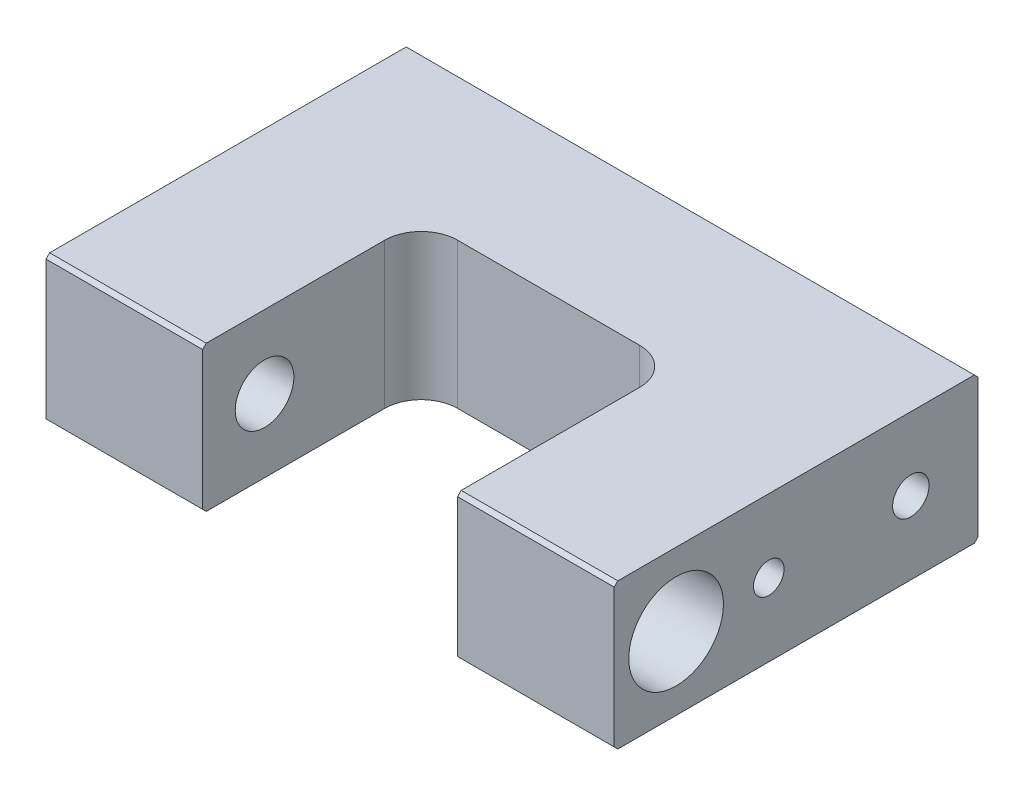
SolidWorks part; units mm, degrees
ref_plane "Front Plane" through (0, 0, 0) normal (0, 0, 1) x (1, 0, 0)
ref_plane "Top Plane" through (0, 0, 0) normal (0, 1, 0) x (1, 0, 0)
ref_plane "Right Plane" through (0, 0, 0) normal (1, 0, 0) x (0, 0, -1)
other "Configuration Table"
sketch "草图1" plane through (0, 0, 0) normal (0, 1, 0) x (1, 0, 0)
  line L1 (-39, 27.2208) -> (39, 27.2208)
  line L2 (-39, 27.2208) -> (-39, -27.2208)
  line L3 (-39, -27.2208) -> (39, -27.2208)
  line L4 (39, 27.2208) -> (39, -27.2208)
  line L5 (-39, 27.2208) -> (39, -27.2208) construction
  line L6 (-39, -27.2208) -> (39, 27.2208) construction
  point P0 (0, 0)
  dimension "D1" = 78
extrude "凸台-拉伸1" add sketch "草图1" along normal blind 20
sketch "草图2" plane through (0, 20, 0) normal (0, 1, 0) x (1, 0, 0)
  line L0 (0, 0) -> (0, -27.2208) construction
  line L1 (-39, -27.2208) -> (39, -27.2208) construction
  line L2 (-17.5, -27.2208) -> (17.5, -27.2208)
  line L3 (-17.5, -27.2208) -> (-17.5, -2.2208)
  line L4 (-12.5, 2.7792) -> (12.5, 2.7792)
  line L5 (17.5, -2.2208) -> (17.5, -27.2208)
  arc A0 (17.5, -2.2208) -> (12.5, 2.7792) centre (12.5, -2.2208) ccw
  arc A1 (-17.5, -2.2208) -> (-12.5, 2.7792) centre (-12.5, -2.2208) cw
  point P8 (0, -27.2208)
  dimension "D1" = 5
extrude "切除-拉伸1" cut sketch "草图2" against normal through all
sketch "草图3" plane through (-39, 0, 0) normal (-1, 0, 0) x (0, 0, 1)
  line L0 (-27.2208, 10) -> (-13.5, 10) construction
  line L1 (-27.2208, 20) -> (-27.2208, 0) construction
  circle A0 centre (-13.5, 10) radius 2.5
  dimension "D1" = 5
extrude "切除-拉伸2" cut sketch "草图3" against normal blind 15
sketch "草图4" plane through (-39, 0, 0) normal (-1, 0, 0) x (0, 0, 1)
  line L0 (-13.5, 10) -> (6, 10) construction
  circle A0 centre (6, 10) radius 2.1
  dimension "D1" = 4.2
extrude "切除-拉伸3" cut sketch "草图4" against normal blind 10
sketch "草图5" plane through (-39, 0, 0) normal (-1, 0, 0) x (0, 0, 1)
  line L0 (27.2208, 10) -> (18.7208, 10) construction
  line L1 (27.2208, 20) -> (27.2208, 0) construction
  circle A0 centre (18.7208, 10) radius 6.5
  dimension "D1" = 8.5
  dimension "D2" = 13
extrude "切除-拉伸4" cut sketch "草图5" against normal blind 12.5
sketch "草图6" plane through (-26.5, 0, 0) normal (-1, 0, 0) x (0, 0, 1)
  circle A0 centre (18.7208, 10) radius 4.025
extrude "切除-拉伸5" cut sketch "草图6" against normal through all
sketch "草图7" plane through (39, 0, 0) normal (1, 0, 0) x (0, 0, -1)
  circle A0 centre (-18.7208, 10) radius 6.5
extrude "切除-拉伸6" cut sketch "草图7" against normal blind 12.5
sketch "草图11" plane through (39, 0, 0) normal (1, 0, 0) x (0, 0, -1)
  line L0 (27.2208, 10) -> (13.5, 10) construction
  line L1 (27.2208, 20) -> (27.2208, 0) construction
  circle A0 centre (13.5, 10) radius 2.5
extrude "切除-拉伸9" cut sketch "草图11" against normal blind 15
sketch "草图12" plane through (39, 0, 0) normal (1, 0, 0) x (0, 0, -1)
  line L0 (13.5, 10) -> (-6, 10) construction
  circle A0 centre (-6, 10) radius 2.1
extrude "切除-拉伸10" cut sketch "草图12" against normal blind 10
sketch "草图9" plane through (-39, 0, 0) normal (-1, 0, 0) x (0, 0, 1)
  line L0 (-27.2208, 0) -> (27.2208, 0) construction
  line L1 (-27.2208, 20) -> (-22.7208, 20)
  line L2 (-27.2208, 20) -> (-27.2208, 0)
  line L3 (-27.2208, 0) -> (-22.7208, 0)
  line L4 (-22.7208, 20) -> (-22.7208, 0)
extrude "切除-拉伸8" cut sketch "草图9" against normal through all
chamfer "倒角3" distance 0.5 angle 45 6 edges at (28.25, 0, 27.2208) (28.25, 20, 27.2208) (-28.25, 0, 27.2208) (-28.25, 20, 27.2208) (0, 0, -22.7208) (0, 20, -22.7208)
